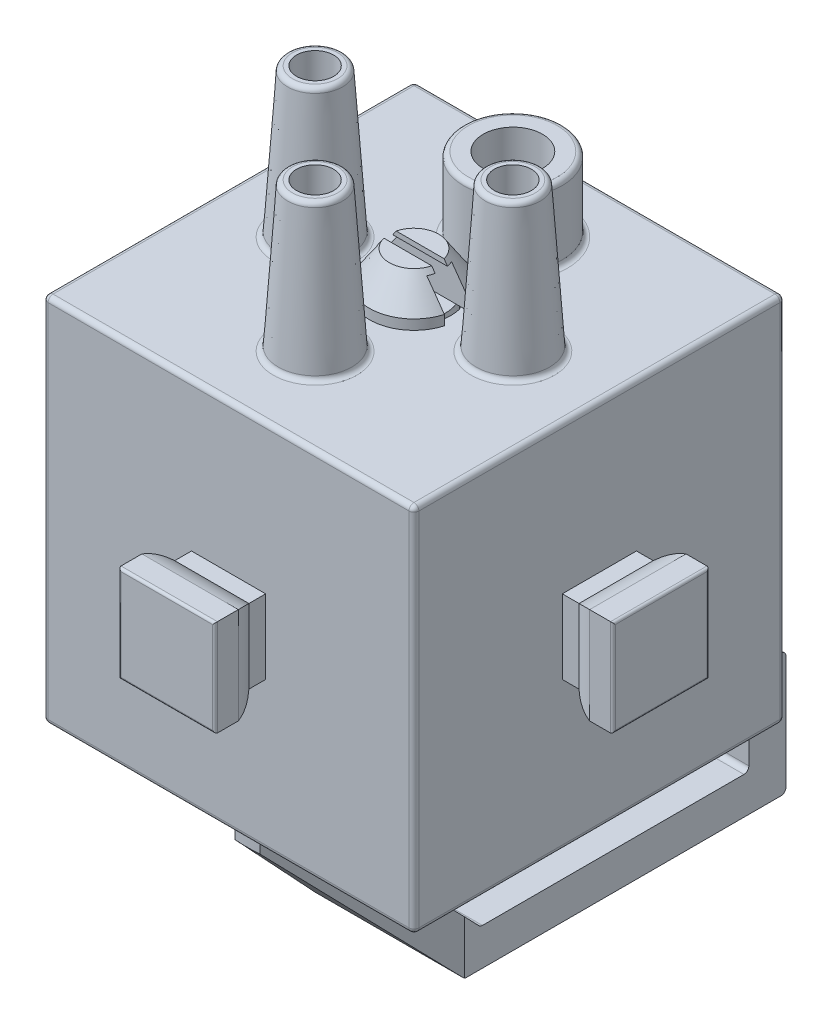
SolidWorks part; units mm, degrees
ref_plane "前视基准面" through (0, 0, 0) normal (0, 0, 1) x (1, 0, 0)
ref_plane "上视基准面" through (0, 0, 0) normal (0, 1, 0) x (1, 0, 0)
ref_plane "右视基准面" through (0, 0, 0) normal (1, 0, 0) x (0, 0, -1)
sketch "草图1" plane through (0, 0, 0) normal (0, 1, 0) x (1, 0, 0)
  line L0 (-7.5, 7.5) -> (-7.5, -7.5)
  line L1 (-7.5, 7.5) -> (7.5, 7.5)
  line L2 (-7.5, -7.5) -> (7.5, -7.5)
  line L3 (7.5, 7.5) -> (7.5, -7.5)
  line L4 (-7.5, 7.5) -> (7.5, -7.5) construction
  line L5 (-7.5, -7.5) -> (7.5, 7.5) construction
  point P1 (0, 0)
  dimension "D1" = 7.5
  dimension "D2" = 15
extrude "凸台-拉伸1" add sketch "草图1" along normal blind 15
sketch "草图2" plane through (0, 0, 0) normal (0, -1, 0) x (1, 0, 0)
  line L0 (0, 7.5) -> (0, 9.5) construction
  line L1 (-7.5, 7.5) -> (7.5, 7.5) construction
  line L2 (0, 9.5) -> (0, 10) construction
  line L3 (-1.95, 10) -> (1.95, 10)
  line L4 (1.95, 10) -> (1.95, 9.0556)
  line L5 (-1.5, 7.5) -> (1.5, 7.5)
  line L6 (1.5, 7.5) -> (1.5, 8.1771)
  line L7 (-1.95, 10) -> (-1.95, 9.0556)
  line L8 (-1.5, 7.5) -> (-1.5, 8.1771)
  arc A1 (1.5, 8.1771) -> (1.95, 9.0556) centre (0, 9.5) ccw
  arc A2 (-1.5, 8.1771) -> (-1.95, 9.0556) centre (0, 9.5) cw
  dimension "D1" = 2
  dimension "D2" = 0.5
  dimension "D3" = 1.95
  dimension "D4" = 1.5
extrude "凸台-拉伸2" add sketch "草图2" against normal blind 15
sketch "草图5" plane through (7.5, 0, 0) normal (1, 0, 0) x (0, 0, -1)
  line L0 (-7.5, 7.5) -> (-9.5, 7.5) construction
  line L1 (-7.5, 15) -> (-7.5, 0) construction
  line L2 (-9.5, 7.5) -> (-10, 7.5) construction
  line L3 (-7.5, 0) -> (-7.5, 6)
  line L4 (-10, 15) -> (-10, 0) construction
  line L5 (-10, 9.45) -> (-9.0556, 9.45)
  line L6 (-10, 0) -> (-7.5, 0)
  line L7 (-7.5, 15) -> (-7.5, 0) construction
  line L8 (-7.5, 9) -> (-8.1771, 9)
  line L9 (-10, 9.45) -> (-10, 15)
  line L10 (-10, 15) -> (-7.5, 15)
  line L11 (-7.5, 15) -> (-7.5, 9)
  line L12 (-10, 5.55) -> (-10, 0)
  line L13 (-7.5, 6) -> (-8.1771, 6)
  line L14 (-10, 5.55) -> (-9.0556, 5.55)
  arc A0 (-8.1771, 9) -> (-9.0556, 9.45) centre (-9.5, 7.5) ccw
  arc A1 (-8.1771, 6) -> (-9.0556, 5.55) centre (-9.5, 7.5) cw
  dimension "D1" = 2
  dimension "D2" = 0.5
  dimension "D3" = 1.95
extrude "切除-拉伸2" cut sketch "草图5" against normal blind 15
sketch "草图6" plane through (0, 0, 0) normal (1, 0, 0) x (0, 0, -1)
  line L0 (0, 0) -> (0, 15) construction
  line L1 (-7.5, 15) -> (7.5, 15) construction
pattern_circular "阵列(圆周)1" count 4 every 90 about axis through (0, 0, 0) along (0, 1, 0) of "凸台-拉伸2", "切除-拉伸2"
sketch "草图7" plane through (0, 0, 0) normal (0, -1, 0) x (1, 0, 0)
  circle A0 centre (0, 0) radius 7
  dimension "D1" = 14
extrude "切除-拉伸3" cut sketch "草图7" against normal blind 5
sketch "草图8" plane through (0, 5, 0) normal (0, -1, 0) x (1, 0, 0)
  circle A0 centre (0, 0) radius 6.75
  dimension "D1" = 13.5
extrude "凸台-拉伸3" add sketch "草图8" along normal blind 5
sketch "草图9" plane through (0, 0, 0) normal (0, -1, 0) x (1, 0, 0)
  line L0 (0, 0) -> (3, 0) construction
  line L1 (3, 0) -> (3, -6.0467) construction
  line L2 (3, -6.0467) -> (3, 0.9533)
  line L3 (0, 0) -> (0.5, 0) construction
  line L4 (0.5, 0) -> (0.5, 6.7315) construction
  line L5 (0.5, 6.7315) -> (3, 0.9533)
  line L6 (0, 0) -> (0, 6.75) construction
  line L7 (-0.5, 6.7315) -> (-3, 0.9533)
  line L8 (-3, -6.0467) -> (-3, 0.9533)
  circle A0 centre (0, 0) radius 6.75 construction
  circle A1 centre (0, 0) radius 6.75 construction
  arc A2 (-3, -6.0467) -> (3, -6.0467) centre (0, 0) ccw
  arc A3 (0.5, 6.7315) -> (-0.5, 6.7315) centre (0, 0) ccw
  dimension "D1" = 3
  dimension "D2" = 7
  dimension "D3" = 0.5
extrude "凸台-拉伸4" add sketch "草图9" along normal blind 2
sketch "草图10" plane through (0, -2, 0) normal (0, -1, 0) x (1, 0, 0)
  line L0 (3, 0.9533) -> (-3, 0.9533) construction
  line L1 (0, 0.9533) -> (0, -12.0467) construction
  line L2 (0, -5.5467) -> (-3, -5.5467) construction
  line L3 (3, -12.0467) -> (-3, -12.0467)
  line L4 (3, -6.0467) -> (3, 0.9533)
  line L5 (3, 0.9533) -> (0.5, 6.7315)
  line L6 (-0.5, 6.7315) -> (-3, 0.9533)
  line L7 (-3, 0.9533) -> (-3, -6.0467)
  line L8 (3, -6.0467) -> (3, 0.9533)
  line L9 (3, 0.9533) -> (0.5, 6.7315)
  line L10 (-0.5, 6.7315) -> (-3, 0.9533)
  line L11 (-3, 0.9533) -> (-3, -6.0467)
  line L12 (-3, -6.0467) -> (-3, -12.0467)
  line L13 (3, -6.0467) -> (3, -12.0467)
  arc A2 (-3, -6.0467) -> (3, -6.0467) centre (0, 0) ccw
  arc A3 (0.5, 6.7315) -> (-0.5, 6.7315) centre (0, 0) ccw
  arc A4 (-3, -6.0467) -> (3, -6.0467) centre (0, 0) ccw construction
  arc A5 (0.5, 6.7315) -> (-0.5, 6.7315) centre (0, 0) ccw
  dimension "D2" = 13
  dimension "D1" = 0
extrude "凸台-拉伸5" add sketch "草图10" along normal blind 5
sketch "草图11" plane through (3, 0, 0) normal (1, 0, 0) x (0, 0, -1)
  line L0 (-6.7315, 0) -> (-6.7315, -1) construction
  line L1 (-6.7315, -7) -> (-6.7315, 0) construction
  line L2 (-6.7315, -1) -> (-0.9533, -7)
  line L4 (-6.7315, -7) -> (-0.9533, -7)
  line L5 (-6.7315, -1) -> (-7.9683, -1)
  line L6 (-7.9683, -1) -> (-7.9683, -7)
  line L7 (-7.9683, -7) -> (-6.7315, -7)
  dimension "D1" = 1
extrude "切除-拉伸4" cut sketch "草图11" against normal through all
sketch "草图12" plane through (-3, 0, 0) normal (-1, 0, 0) x (0, 0, 1)
  line L16 (-6.0467, -3.5) -> (-10.5467, -3.5)
  line L17 (-10.5467, -3.5) -> (-10.5467, -5.5)
  line L18 (-10.5467, -5.5) -> (0.3154, -5.5)
  line L19 (0.3154, -5.5) -> (2.2414, -3.5)
  line L21 (-6.0467, -3.5) -> (2.2414, -3.5)
  line L22 (-5.0467, -0.5) -> (-5.0467, -2)
  line L23 (5.1305, -0.5) -> (0.9533, -0.5)
  line L24 (0.9533, -0.5) -> (-5.0467, -0.5)
  line L25 (-5.0467, -2) -> (3.686, -2)
  line L27 (3.686, -2) -> (5.1305, -0.5)
  point P12 (5.2315, -0.3952)
  point P17 (6.7315, -0.5)
  point P19 (-6.0467, -0.5)
extrude "切除-拉伸5" cut sketch "草图12" against normal blind 2
mirror "镜向1" about plane through (0, 0, 0) normal (1, 0, 0) of "切除-拉伸5"
sketch "草图13" plane through (0, 15, 0) normal (0, 1, 0) x (1, 0, 0)
  line L0 (0, 0) -> (4, 0) construction
  circle A0 centre (0, 0) radius 4 construction
  circle A1 centre (4, 0) radius 1.5
  dimension "D1" = 8
  dimension "D2" = 3
ref_plane "基准面1" through (0, 21, 0) normal (0, 1, 0) x (1, 0, 0)
sketch "草图14" plane through (0, 21, 0) normal (0, 1, 0) x (1, 0, 0)
  circle A0 centre (4, 0) radius 1.1
  dimension "D1" = 2.2
loft "放样2" add profiles "草图14", "草图13"
sketch "草图15" plane through (0, 21, 0) normal (0, 1, 0) x (1, 0, 0)
  circle A2 centre (4, 0) radius 0.75
  circle A3 centre (4, 0) radius 0.75
  dimension "D1" = 0.35
extrude "切除-拉伸6" cut sketch "草图15" against normal blind 6
pattern_circular "阵列(圆周)3" count 3 every 90 about axis through (0, 0, 0) along (0, 1, 0) of "切除-拉伸6", "放样2"
sketch "草图16" plane through (0, 15, 0) normal (0, 1, 0) x (1, 0, 0)
  line L0 (0, 0) -> (0, 4) construction
  circle A0 centre (0, 0) radius 4 construction
  circle A1 centre (0, 4) radius 2
  circle A2 centre (0, 4) radius 1.2
  dimension "D1" = 8
  dimension "D2" = 4
  dimension "D3" = 2.4
extrude "凸台-拉伸6" add sketch "草图16" along normal blind 3
fillet "圆角1" radius 0.2 12 edges at (7.5, 7.5, -7.5) (7.5, 7.5, 7.5) (-7.5, 7.5, 7.5) (-7.5, 7.5, -7.5)
fillet "圆角2" radius 0.2 16 edges at (2, -5.5, -10.5467) (2, -3.5, -10.5467) (2, -5.5, 0.3154) (1.7213, -3.5, 2.2414) (2, -2, -5.0467) (2, -0.5, -5.0467) (1.4088, -2, 3.686) (1.0963, -0.5, 5.1305) (-2, -5.5, -10.5467) (-2, -3.5, -10.5467) (-2, -5.5, 0.3154) (-1.7213, -3.5, 2.2414) (-2, -2, -5.0467) (-2, -0.5, -5.0467) (-1.4088, -2, 3.686) (-1.0963, -0.5, 5.1305)
fillet "圆角5" radius 0.2 3 edges at (0, -7, 0.9533) (0, -7, -12.0467) (0, -2, -12.0467)
fillet "圆角7" radius 0.2 8 edges at (4, 21, 1.1) (4, 15, 1.5) (-1.1, 21, 4) (-1.5, 15, 4) (-4, 21, -1.1) (-4, 15, -1.5) (0, 15, -6) (0, 18, -2)
fillet "圆角8" radius 0.1 16 edges at (0, 9.45, -10) (-1.95, 7.5, -10) (0, 5.55, -10) (1.95, 7.5, -10) (-10, 5.55, 0) (-10, 7.5, -1.95) (-10, 9.45, 0) (-10, 7.5, 1.95) (-1.95, 7.5, 10) (0, 5.55, 10) (0, 9.45, 10) (1.95, 7.5, 10) (10, 7.5, 1.95) (10, 9.45, 0) (10, 7.5, -1.95) (10, 5.55, 0)
sketch "草图17" plane through (0, 15, 0) normal (0, 1, 0) x (1, 0, 0)
  circle A0 centre (0, 0) radius 1.5
  dimension "D1" = 3
extrude "切除-拉伸7" cut sketch "草图17" against normal blind 10
sketch "草图18" plane through (0, 5, 0) normal (0, 1, 0) x (1, 0, 0)
  circle A0 centre (0, 0) radius 1.3
  dimension "D1" = 2.6
extrude "凸台-拉伸7" add sketch "草图18" along normal blind 10
sketch "草图20" plane through (0, 15, 0) normal (0, 1, 0) x (1, 0, 0)
  circle A0 centre (0, 0) radius 1.8
  dimension "D1" = 3.6
ref_plane "基准面2" through (0, 16.6, 0) normal (0, 1, 0) x (1, 0, 0)
sketch "草图22" plane through (0, 16.6, 0) normal (0, 1, 0) x (1, 0, 0)
  circle A0 centre (0, 0) radius 1
  dimension "D1" = 2
extrude "凸台-拉伸8" add sketch "草图20" along normal blind 0.4
sketch "草图23" plane through (0, 15.4, 0) normal (0, 1, 0) x (1, 0, 0)
  circle A1 centre (0, 0) radius 1.8
  circle A2 centre (0, 0) radius 1.8
  dimension "D1" = 0
loft "放样4" add profiles "草图23", "草图22"
sketch "草图24" plane through (0, 0, 0) normal (1, 0, 0) x (0, 0, -1)
  line L0 (0, 16.8) -> (0, 15) construction
  line L1 (-0.5, 15) -> (-0.5, 16.4)
  line L2 (-0.5, 15) -> (0.5, 15)
  line L3 (0.5, 15) -> (0.5, 16.4)
  line L4 (-0.25, 16.8) -> (0.25, 16.8)
  line L5 (0.25, 16.8) -> (0.25, 16.4)
  line L6 (0.25, 16.4) -> (0.5, 16.4)
  line L7 (-0.25, 16.8) -> (-0.25, 16.4)
  line L8 (-0.5, 16.4) -> (-0.25, 16.4)
  dimension "D1" = 1.8
  dimension "D3" = 0.5
  dimension "D4" = 1.4
  dimension "D5" = 0.25
extrude "切除-拉伸8" cut sketch "草图24" against normal blind 2 and the other way blind 2
